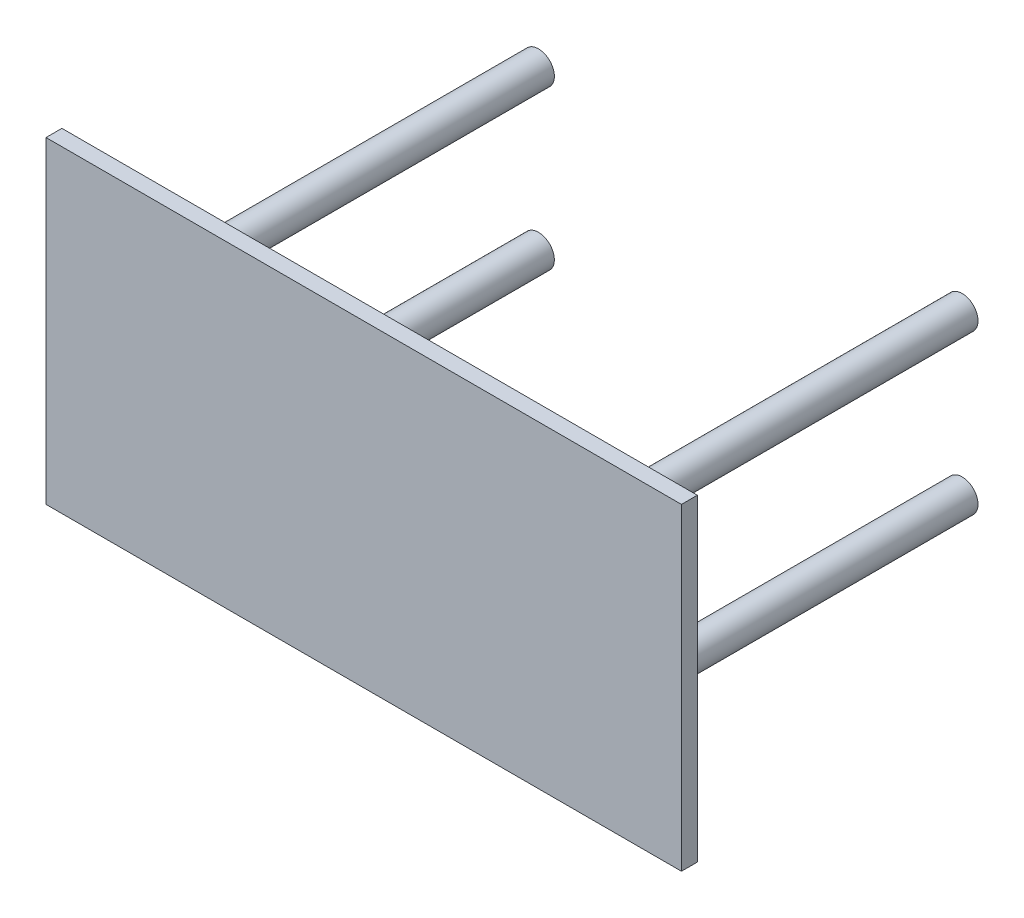
SolidWorks part; units mm, degrees
ref_plane "前视基准面" through (0, 0, 0) normal (0, 0, 1) x (1, 0, 0)
ref_plane "上视基准面" through (0, 0, 0) normal (0, 1, 0) x (1, 0, 0)
ref_plane "右视基准面" through (0, 0, 0) normal (1, 0, 0) x (0, 0, -1)
sketch "草图1" plane through (0, 0, 0) normal (0, 0, 1) x (1, 0, 0)
  line L1 (-60, -30) -> (60, -30)
  line L2 (-60, -30) -> (-60, 30)
  line L3 (-60, 30) -> (60, 30)
  line L4 (60, -30) -> (60, 30)
  line L5 (-60, -30) -> (60, 30) construction
  line L6 (-60, 30) -> (60, -30) construction
  point P0 (0, 0)
  dimension "D1" = 60
  dimension "D2" = 120
extrude "凸台-拉伸1" add sketch "草图1" along normal blind 3
sketch "草图2" plane through (0, 0, 0) normal (0, 0, -1) x (-1, 0, 0)
  line L0 (0, 43.1971) -> (0, -50.0537) construction
  line L1 (-76.6119, 0) -> (71.0352, 0) construction
  circle A0 centre (-40, 15) radius 3
  circle A1 centre (40, 15) radius 3
  circle A2 centre (40, -15) radius 3
  circle A3 centre (-40, -15) radius 3
  dimension "D1" = 80
  dimension "D2" = 30
  dimension "D3" = 6
extrude "凸台-拉伸2" add sketch "草图2" along normal blind 70
